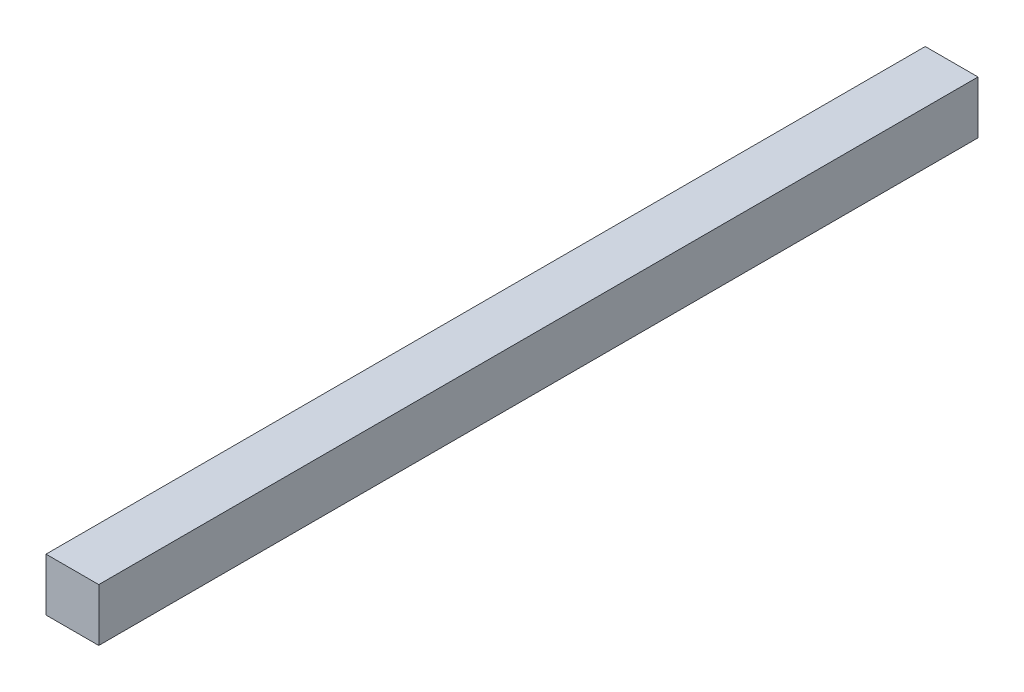
SolidWorks part; units mm, degrees
ref_plane "Front Plane" through (0, 0, 0) normal (0, 0, 1) x (1, 0, 0)
ref_plane "Top Plane" through (0, 0, 0) normal (0, 1, 0) x (1, 0, 0)
ref_plane "Right Plane" through (0, 0, 0) normal (1, 0, 0) x (0, 0, -1)
sketch "Sketch1" plane through (0, 0, 0) normal (0, 0, 1) x (1, 0, 0)
  line L1 (-19.5762, 22.7172) -> (10.4238, 22.7172)
  line L2 (-19.5762, 22.7172) -> (-19.5762, -7.2828)
  line L3 (-19.5762, -7.2828) -> (10.4238, -7.2828)
  line L4 (10.4238, 22.7172) -> (10.4238, -7.2828)
  dimension "D1" = 30
  dimension "D2" = 30
extrude "Boss-Extrude1" add sketch "Sketch1" along normal blind 500
